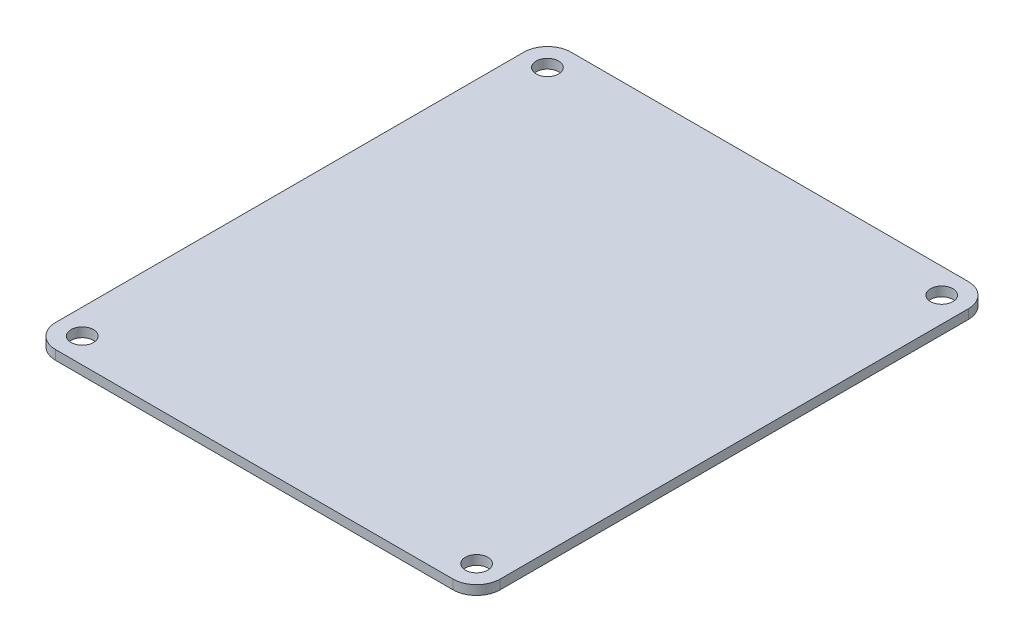
SolidWorks part; units mm, degrees
ref_plane "Front Plane" through (0, 0, 0) normal (0, 0, 1) x (1, 0, 0)
ref_plane "Top Plane" through (0, 0, 0) normal (0, 1, 0) x (1, 0, 0)
ref_plane "Right Plane" through (0, 0, 0) normal (1, 0, 0) x (0, 0, -1)
sketch "Sketch2" plane through (0, 0, 0) normal (0, 1, 0) x (1, 0, 0)
  circle A0 centre (33.4, -71.7648) radius 1.9 construction
  circle A1 centre (-33.4, -71.7648) radius 1.9 construction
  circle A2 centre (-33.4, 7.0352) radius 1.9 construction
  circle A3 centre (33.4, 7.0352) radius 1.9 construction
  circle A4 centre (33.4, -71.7648) radius 1.9
  circle A5 centre (-33.4, -71.7648) radius 1.9
  circle A6 centre (-33.4, 7.0352) radius 1.9
  circle A7 centre (33.4, 7.0352) radius 1.9
sketch "Sketch1" plane through (0, 0, 0) normal (0, 1, 0) x (1, 0, 0)
  line L6 (-37.65, 11.2852) -> (37.65, 11.2852)
  line L8 (-37.65, 11.2852) -> (-37.65, -76.0148)
  line L9 (-37.65, -76.0148) -> (37.65, -76.0148)
  line L10 (37.65, 11.2852) -> (37.65, -76.0148)
  circle A0 centre (-33.4, 7.0352) radius 4.25 construction
  circle A1 centre (33.4, 7.0352) radius 4.25 construction
  circle A3 centre (33.4, -71.7648) radius 4.25 construction
  circle A4 centre (-33.4, -71.7648) radius 4.25 construction
  circle A5 centre (33.4, 7.0352) radius 2.5 construction
  dimension "D1" = 1.75
  dimension "D2" = 5
extrude "Boss-Extrude1" add sketch "Sketch1" along normal blind 1.5875
extrude "Cut-Extrude1" cut sketch "Sketch2" along normal up to surface (1.5875 mm away) up to face at (0, 1.5875, 32.3648)
fillet "Fillet1" radius 4 4 edges at (37.65, 0.7937, 76.0148) (-37.65, 0.7937, 76.0148) (37.65, 0.7937, -11.2852) (-37.65, 0.7937, -11.2852)
